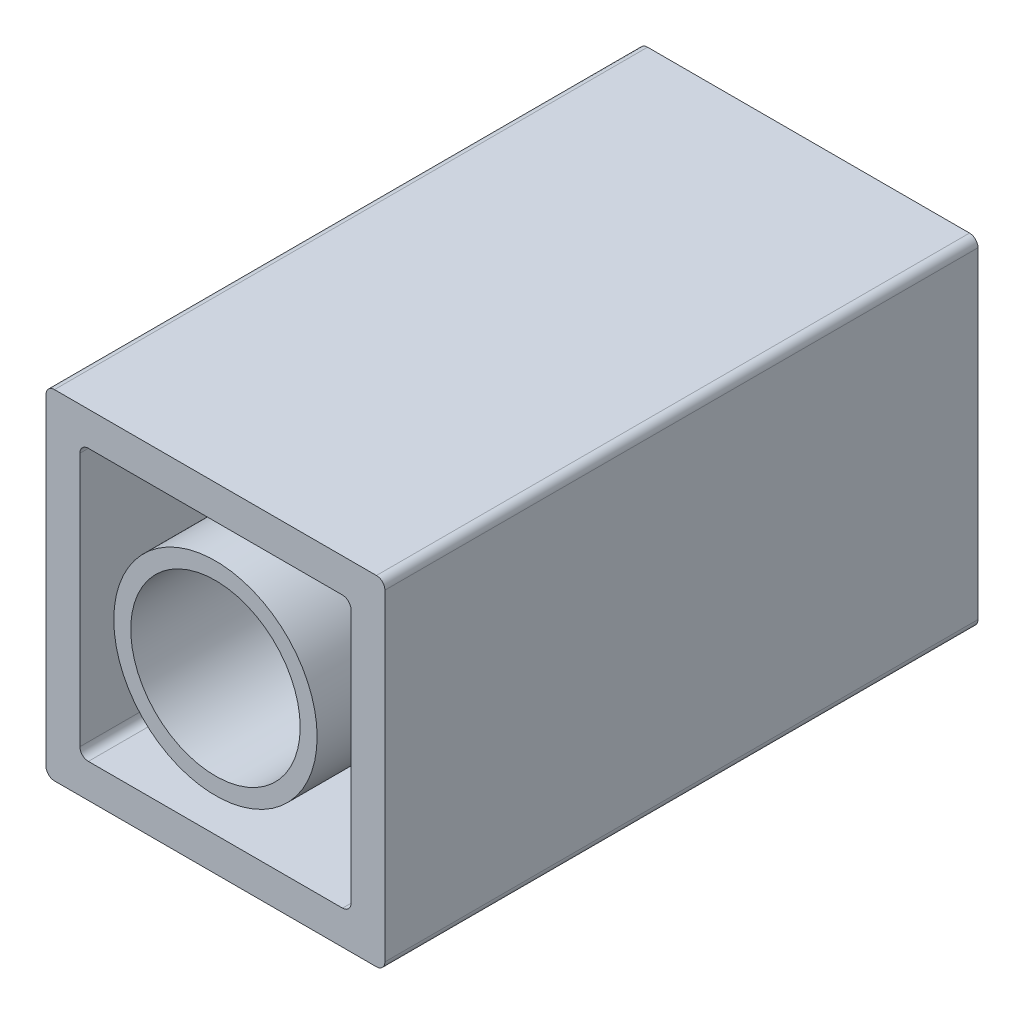
SolidWorks part; units mm, degrees
material "Plastique personnalisé"
ref_plane "Plan de face" through (0, 0, 0) normal (0, 0, 1) x (1, 0, 0)
ref_plane "Plan de dessus" through (0, 0, 0) normal (0, 1, 0) x (1, 0, 0)
ref_plane "Plan de droite" through (0, 0, 0) normal (1, 0, 0) x (0, 0, -1)
sketch "Esquisse1" plane through (0, 0, 0) normal (0, 0, 1) x (1, 0, 0)
  line L0 (10, -10) -> (-10, 10) construction
  line L1 (-10, 10) -> (10, 10)
  line L2 (-10, 10) -> (-10, -10)
  line L3 (-10, -10) -> (10, -10)
  line L4 (10, 10) -> (10, -10)
  line L5 (10, 10) -> (-10, -10) construction
  dimension "D1" = 20
  dimension "D2" = 20
extrude "Boss.-Extru.1" add sketch "Esquisse1" along normal blind 35
shell "Coque2" thickness 2
fillet "Congé1" radius 0.5 8 edges at (8, 8, 18.5) (8, -8, 18.5) (-8, -8, 18.5) (-8, 8, 18.5) (-10, -10, 17.5) (10, -10, 17.5) (-10, 10, 17.5) (10, 10, 17.5)
sketch "Esquisse2" plane through (0, 0, 2) normal (0, 0, 1) x (1, 0, 0)
  line L0 (-9.8536, 9.8536) -> (9.8536, -9.8536) construction
  line L1 (9.8536, 9.8536) -> (-9.8536, -9.8536) construction
  arc A0 (-9.5, 10) -> (-10, 9.5) centre (-9.5, 9.5) ccw construction
  arc A1 (9.5, -10) -> (10, -9.5) centre (9.5, -9.5) ccw construction
  arc A2 (10, 9.5) -> (9.5, 10) centre (9.5, 9.5) ccw construction
  arc A3 (-10, -9.5) -> (-9.5, -10) centre (-9.5, -9.5) ccw construction
  circle A4 centre (0, 0) radius 6
  dimension "D1" = 12
extrude "Boss.-Extru.2" add sketch "Esquisse2" along normal up to surface (33 mm away) up to face at (0, 0, 35)
sketch "Esquisse3" plane through (0, 0, 35) normal (0, 0, 1) x (1, 0, 0)
  circle A0 centre (0, 0) radius 5
  dimension "D1" = 10
extrude "Enlèv. mat.-Extru.3" cut sketch "Esquisse3" against normal up to surface (33 mm away) up to face at (6, 0, 2)
fillet "Congé2" radius 0.8 1 edges at (6, 0, 2)
